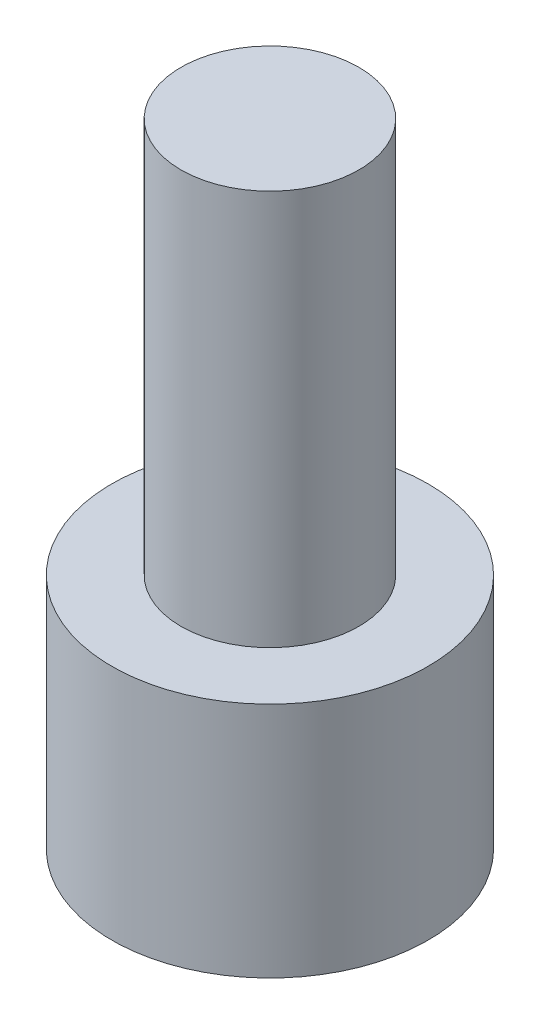
SolidWorks part; units mm, degrees
ref_plane "Plano frontal" through (0, 0, 0) normal (0, 0, 1) x (1, 0, 0)
ref_plane "Plano superior" through (0, 0, 0) normal (0, 1, 0) x (1, 0, 0)
ref_plane "Plano direito" through (0, 0, 0) normal (1, 0, 0) x (0, 0, -1)
sketch "Esboço1" plane through (0, 0, 0) normal (0, 1, 0) x (1, 0, 0)
  circle A0 centre (0, 0) radius 2.25
  dimension "D1" = 4.5
extrude "Ressalto-extrusão1" add sketch "Esboço1" along normal blind 10
sketch "Esboço3" plane through (0, 0, 0) normal (0, -1, 0) x (1, 0, 0)
  circle A0 centre (0, 0) radius 4
  dimension "D1" = 8
extrude "Ressalto-extrusão2" add sketch "Esboço3" along normal blind 6
sketch "Esboço4" plane through (0, -6, 0) normal (0, -1, 0) x (1, 0, 0)
  circle A0 centre (0, 0) radius 2.25
  dimension "D1" = 4.5
extrude "Corte-extrusão1" cut sketch "Esboço4" against normal blind 2
